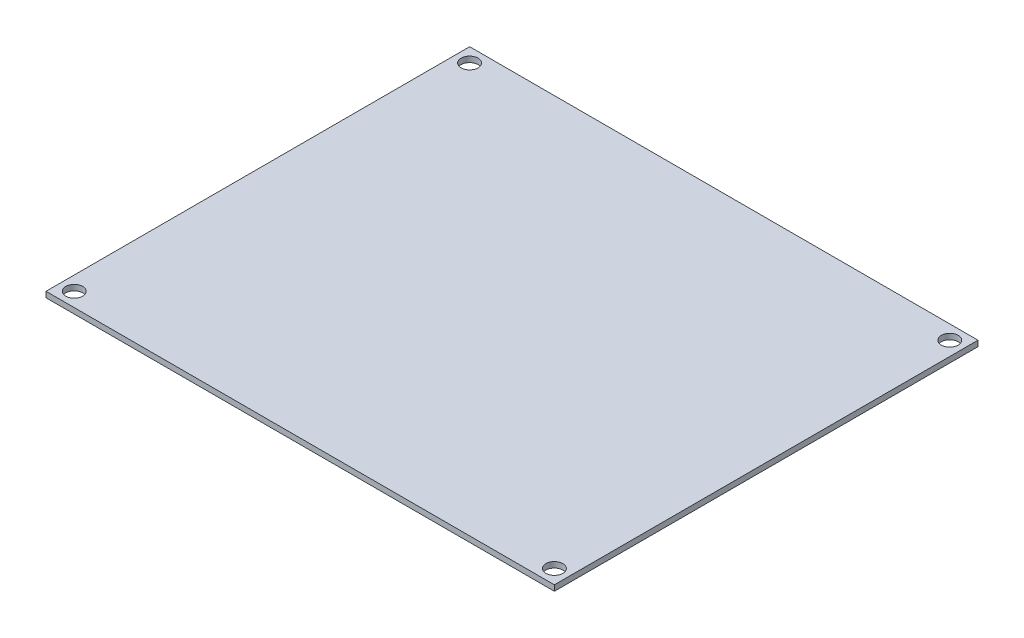
SolidWorks part; units mm, degrees
material "ABS"
ref_plane "Спереди" through (0, 0, 0) normal (0, 0, 1) x (1, 0, 0)
ref_plane "Сверху" through (0, 0, 0) normal (0, 1, 0) x (1, 0, 0)
ref_plane "Справа" through (0, 0, 0) normal (1, 0, 0) x (0, 0, -1)
sketch "Sketch1" plane through (0, 0, 0) normal (0, 1, 0) x (1, 0, 0)
  line L0 (-85, -1080) -> (-85, 48920)
  line L3 (-90, 65) -> (90, 65)
  line L5 (-90, 65) -> (-90, -85)
  line L6 (-90, -85) -> (90, -85)
  line L7 (90, 65) -> (90, -85)
  circle A0 centre (-85, -80) radius 3
  circle A1 centre (85, -80) radius 3
  circle A2 centre (-85, 60) radius 3
  circle A3 centre (85, 60) radius 3
  point P0 (-85, 65)
extrude "Boss-Extrude1" add sketch "Sketch1" along normal blind 2
